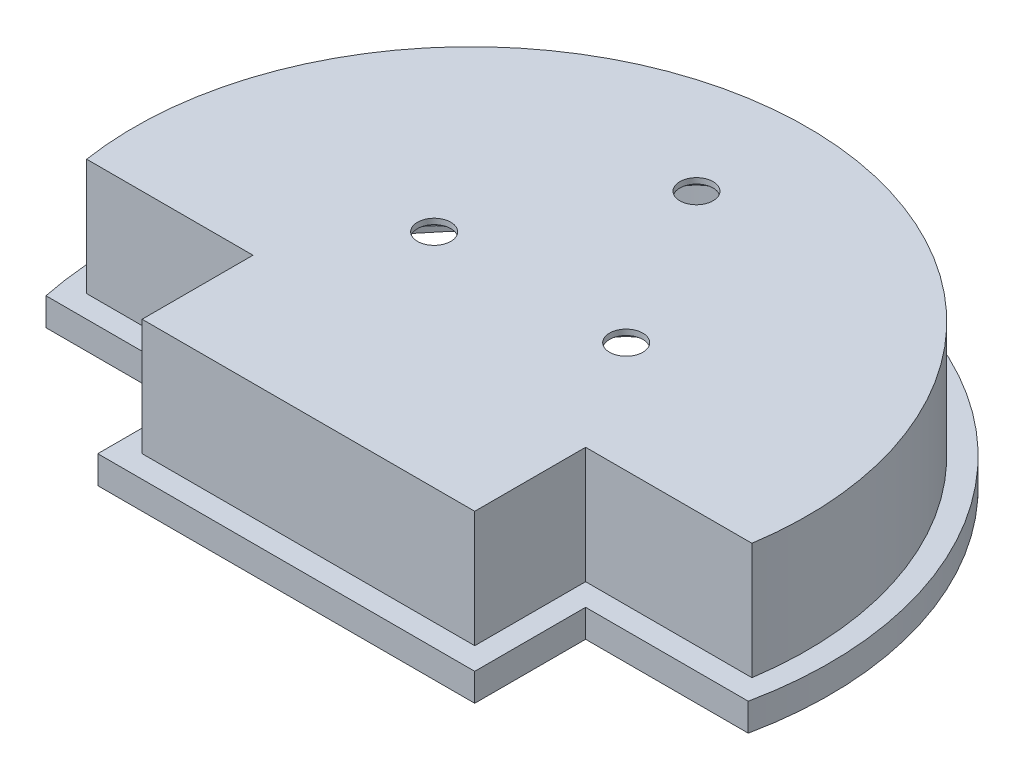
SolidWorks part; units mm, degrees
ref_plane "Alzado" through (0, 0, 0) normal (0, 0, 1) x (1, 0, 0)
ref_plane "Planta" through (0, 0, 0) normal (0, 1, 0) x (1, 0, 0)
ref_plane "Vista lateral" through (0, 0, 0) normal (1, 0, 0) x (0, 0, -1)
sketch "Croquis1" plane through (0, 0, 0) normal (0, 1, 0) x (1, 0, 0)
  line L0 (0, 0) -> (0, 36.4718) construction
  line L1 (-15, 0) -> (15, 0)
  line L2 (-15, 0) -> (-15, 10)
  line L3 (15, 0) -> (15, 10)
  line L4 (-15, 10) -> (-30, 10)
  line L5 (15, 10) -> (30, 10)
  arc A0 (-30, 10) -> (30, 10) centre (0, 14.6429) cw
  point P10 (0, 45)
  dimension "D4" = 35
  dimension "D1" = 30
  dimension "D2" = 10
  dimension "D3" = 15
extrude "Extruir-Lámina1" add sketch "Croquis1" along normal blind 11 thin thin type one direction reverse wall 2
sketch "Croquis2" plane through (0, 11, 0) normal (0, 1, 0) x (1, 0, 0)
  line L0 (15, 10) -> (30, 10) construction
  line L1 (15, 0) -> (15, 10) construction
  line L2 (-15, 0) -> (15, 0) construction
  line L3 (-15, 10) -> (-15, 0) construction
  line L4 (-30, 10) -> (-15, 10) construction
  line L5 (15, 10) -> (30, 10)
  line L6 (15, 0) -> (15, 10)
  line L7 (-15, 0) -> (15, 0)
  line L8 (-15, 10) -> (-15, 0)
  line L9 (-30, 10) -> (-15, 10)
  arc A0 (30, 10) -> (-30, 10) centre (0, 14.6429) ccw construction
  arc A1 (30, 10) -> (-30, 10) centre (0, 14.6429) ccw
extrude "Saliente-Extruir1" add sketch "Croquis2" along normal blind 2
sketch "Croquis3" plane through (0, 11, 0) normal (0, -1, 0) x (1, 0, 0)
  line L0 (0, -20) -> (0, -35) construction
  line L1 (-8.6603, -20) -> (8.6603, -20) construction
  line L2 (8.6603, -20) -> (0, -35) construction
  line L3 (0, -35) -> (-8.6603, -20) construction
  circle A0 centre (-8.6603, -20) radius 3.5
  circle A1 centre (8.6603, -20) radius 3.5
  circle A2 centre (0, -35) radius 3.5
  arc A3 (-30, -10) -> (30, -10) centre (0, -14.6429) ccw construction
  point P11 (0, -45)
  point P12 (0, -27.5)
  dimension "D2" = 7
  dimension "D1" = 15
  dimension "D3" = 27.5
extrude "Cortar-Extruir2" cut sketch "Croquis3" against normal blind 1.5
sketch "Croquis4" plane through (0, 0, 0) normal (0, -1, 0) x (1, 0, 0)
  line L0 (17, 2) -> (-17, 2)
  line L1 (-17, 2) -> (-17, -8)
  line L2 (-17, -8) -> (-31.6679, -8)
  line L3 (31.6679, -8) -> (17, -8)
  line L4 (17, -8) -> (17, 2)
  line L6 (13, -12) -> (28.2337, -12) construction
  line L15 (13, -2) -> (13, -12) construction
  line L16 (-13, -2) -> (13, -2) construction
  line L17 (-28.2337, -12) -> (-13, -12) construction
  line L18 (-13, -12) -> (-13, -2) construction
  line L19 (13, -12) -> (28.2337, -12)
  line L20 (13, -2) -> (13, -12)
  line L21 (-13, -2) -> (13, -2)
  line L22 (-28.2337, -12) -> (-13, -12)
  line L23 (-13, -12) -> (-13, -2)
  arc A0 (-31.6679, -8) -> (31.6679, -8) centre (0, -14.6429) ccw
  arc A3 (-28.2337, -12) -> (28.2337, -12) centre (0, -14.6429) ccw construction
  arc A4 (-28.2337, -12) -> (28.2337, -12) centre (0, -14.6429) ccw
extrude "Saliente-Extruir3" add sketch "Croquis4" against normal blind 2.5
sketch "Croquis5" plane through (0, 11, 0) normal (0, -1, 0) x (1, 0, 0)
  circle A0 centre (-8.6603, -20) radius 1.5
  circle A1 centre (8.6603, -20) radius 1.5
  circle A2 centre (0, -35) radius 1.5
  dimension "D1" = 3
extrude "Cortar-Extruir3" cut sketch "Croquis5" against normal blind 10
